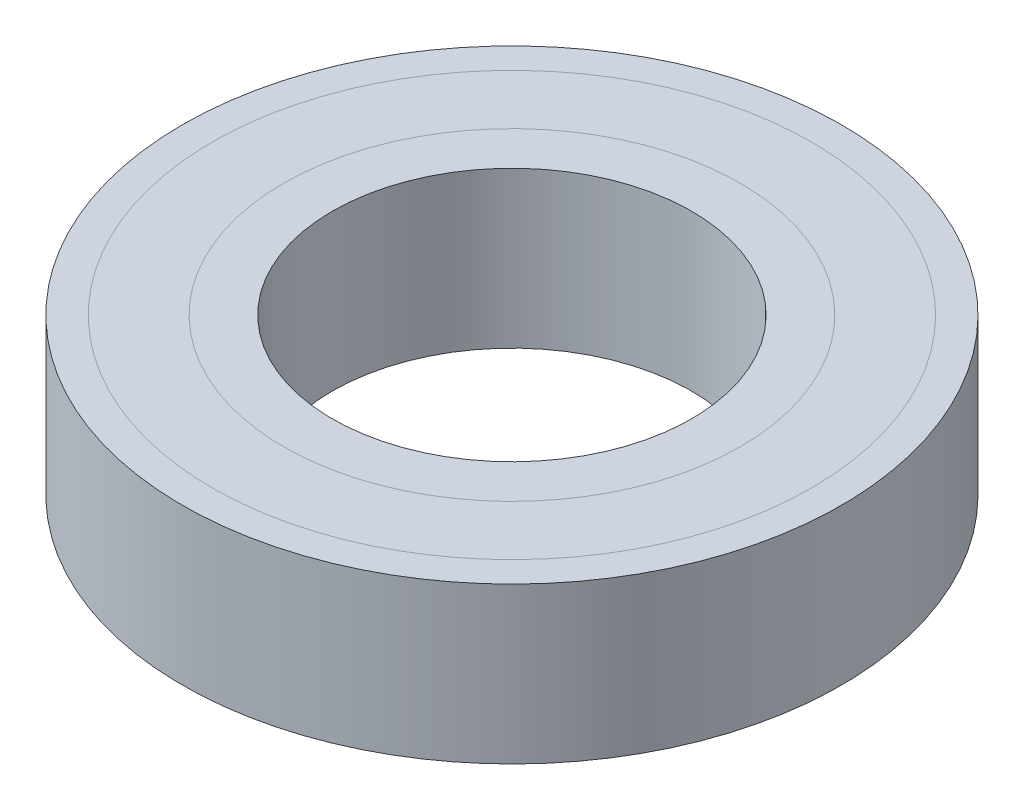
SolidWorks part; units mm, degrees
other "Markup1"
sketch "Sketch2" plane through (-62, 8, 62) normal (-0.7232, 0.6558, 0.2165) x (0.3413, 0.6119, -0.7135)
sketch "Sketch3" plane through (-31, 8, 31) normal (-0.7232, 0.6558, 0.2165) x (0.3413, 0.6119, -0.7135)
sketch "Sketch5" plane through (-27.5, 6.5, 27.5) normal (-0.7232, 0.6558, 0.2165) x (0.3413, 0.6119, -0.7135)
sketch "Sketch6" plane through (-27.5, 6.5, 27.5) normal (-0.7232, 0.6558, 0.2165) x (0.3413, 0.6119, -0.7135)
ref_plane "Front Plane" through (0, 0, 0) normal (0, 0, 1) x (1, 0, 0)
ref_plane "Top Plane" through (0, 0, 0) normal (0, 1, 0) x (1, 0, 0)
ref_plane "Right Plane" through (0, 0, 0) normal (1, 0, 0) x (0, 0, -1)
sketch "Sketch1" plane through (0, 0, 0) normal (0, 0, 1) x (1, 0, 0)
  line L0 (0, 0) -> (15, 0) construction
  line L1 (0, 6.5) -> (0, -6.5) construction
  line L2 (15, -6.5) -> (27.5, -6.5)
  line L3 (15, -6.5) -> (15, 6.5)
  line L4 (15, 6.5) -> (27.5, 6.5)
  line L5 (27.5, -6.5) -> (27.5, 6.5)
  line L6 (15, -6.5) -> (27.5, 6.5) construction
  line L7 (15, 6.5) -> (27.5, -6.5) construction
  point P2 (21.25, 0)
  point P4 (0, 0)
  point P10 (0, 0)
  point P11 (15, 0)
  point P15 (27.5, 0)
  dimension "D3" = 13
  dimension "D1" = 15
  dimension "D2" = 27.5
revolve "Revolve1" add sketch "Sketch1" angle 360 about L1
sketch "Sketch4" plane through (0, 0, 0) normal (0, 1, 0) x (1, 0, 0)
  circle A0 centre (0, 0) radius 25
  circle A1 centre (0, 0) radius 19.05
  dimension "D1" = 50
  dimension "D2" = 38.1
split line "Split Line1"
equation "\"OD\"= 55mm"
equation "\"ID\"= 30mm"
equation "\"Depth\"= 13mm"
equation "\"D3@Sketch1\"=\"Depth\""
equation "\"D1@Sketch1\"=\"ID\"/2"
equation "\"D2@Sketch1\"=\"OD\"/2"
equation "\"OD Abutment\"= 50mm"
equation "\"ID Abutment\"= 38.1mm"
equation "\"D1@Sketch4\"=\"OD Abutment\""
equation "\"D2@Sketch4\"=\"ID Abutment\""
